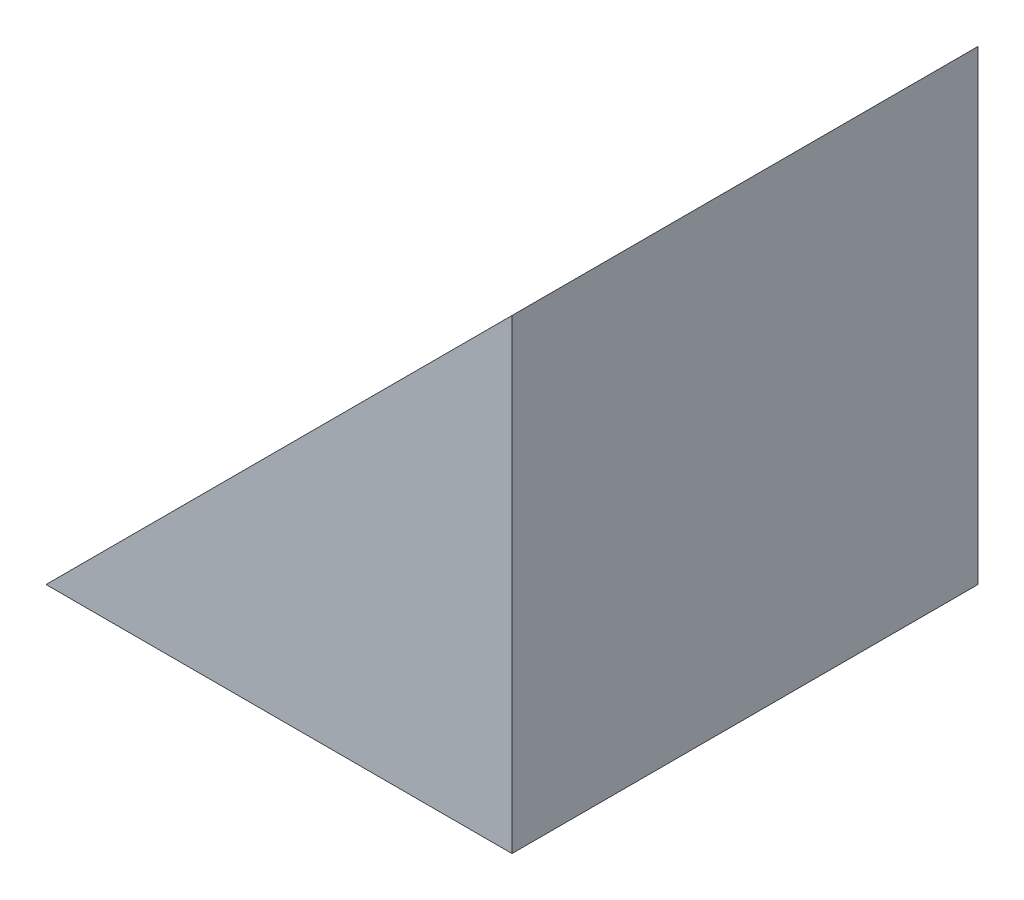
SolidWorks part; units mm, degrees
ref_plane "Front Plane" through (0, 0, 0) normal (0, 0, 1) x (1, 0, 0)
ref_plane "Top Plane" through (0, 0, 0) normal (0, 1, 0) x (1, 0, 0)
ref_plane "Right Plane" through (0, 0, 0) normal (1, 0, 0) x (0, 0, -1)
sketch "Sketch1" plane through (0, 0, 0) normal (0, 0, 1) x (1, 0, 0)
  line L1 (-4.6614, -41.6391) -> (-2.6614, -41.6391)
  line L2 (-4.6614, -41.6391) -> (-4.6614, -43.6391)
  line L3 (-4.6614, -43.6391) -> (-2.6614, -43.6391)
  line L4 (-2.6614, -41.6391) -> (-2.6614, -43.6391)
  line L5 (-4.6614, -41.6391) -> (-2.6614, -43.6391) construction
  line L6 (-4.6614, -43.6391) -> (-2.6614, -41.6391) construction
  point P0 (-3.6614, -42.6391)
  dimension "D1" = 2
  dimension "D2" = 2
extrude "Boss-Extrude1" add sketch "Sketch1" along normal blind 2
sketch "Sketch2" plane through (0, 0, 2) normal (0, 0, 1) x (1, 0, 0)
  line L0 (-4.6614, -43.6391) -> (-2.6614, -41.6391)
  line L1 (-2.6614, -41.6391) -> (-4.6614, -41.6391)
  line L2 (-2.6614, -41.6391) -> (-4.6614, -41.6391) construction
  line L3 (-4.6614, -41.6391) -> (-4.6614, -43.6391) construction
  line L4 (-4.6614, -41.6391) -> (-4.6614, -43.6391)
extrude "Cut-Extrude1" cut sketch "Sketch2" against normal through all
sketch "Sketch3" plane through (19.4888, -19.4888, 0) normal (-0.7071, 0.7071, 0) x (0, 0, 1)
  line L0 (2, -32.7394) -> (0, -32.7394) construction
  line L1 (2, -34.1536) -> (2, -31.3252) construction
  line L2 (0, -34.1536) -> (0, -31.3252) construction
  line L3 (0, -32.7394) -> (1, -34.1536) construction
  line L4 (2, -34.1536) -> (0, -34.1536) construction
  line L5 (1, -34.1536) -> (1, -31.3252) construction
  line L6 (2, -31.3252) -> (0, -31.3252) construction
  line L7 (1, -31.3252) -> (2, -32.7394) construction
  line L8 (2, -32.7394) -> (1, -34.1536) construction
  line L9 (1, -31.3252) -> (0, -32.7394) construction
  point P6 (1, -32.7394)
equation "\"D2@Sketch1\"=\"D1@Sketch1\""
